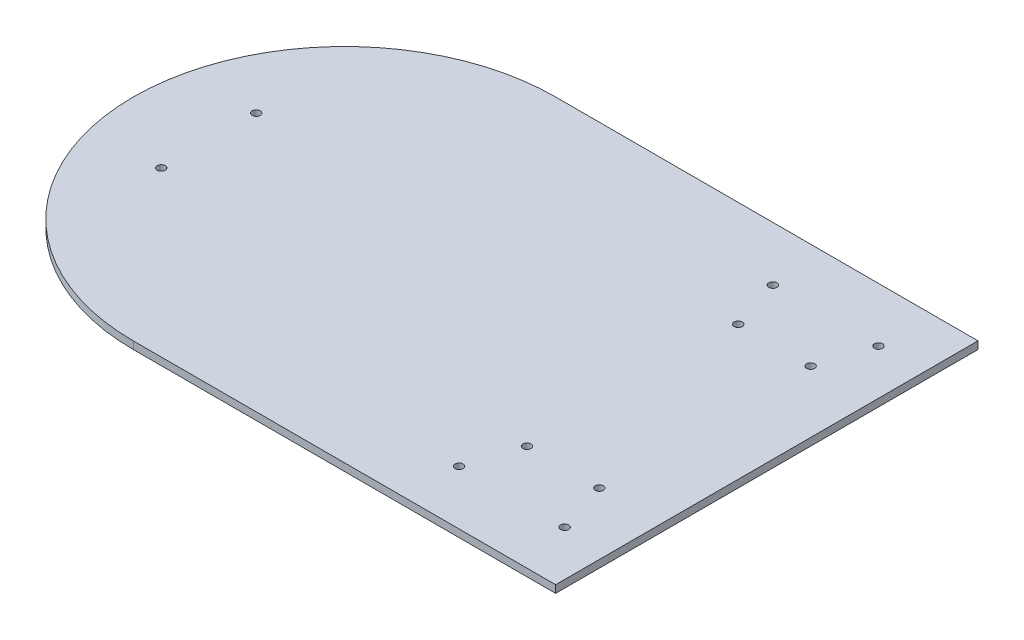
SolidWorks part; units mm, degrees
material "Acrylic (Medium-high impact)"
ref_plane "Front Plane" through (0, 0, 0) normal (0, 0, 1) x (1, 0, 0)
ref_plane "Top Plane" through (0, 0, 0) normal (0, 1, 0) x (1, 0, 0)
ref_plane "Right Plane" through (0, 0, 0) normal (1, 0, 0) x (0, 0, -1)
sketch "Sketch2" plane through (0, 0, 0) normal (0, 1, 0) x (1, 0, 0)
  line L0 (0, 0) -> (0, 177.8)
  line L1 (0, 177.8) -> (-177.8, 177.8)
  line L2 (0, 0) -> (-177.8, 0)
  line L3 (-177.8, 177.8) -> (-177.8, 0) construction
  arc A0 (-177.8, 177.8) -> (-177.8, 0) centre (-177.8, 88.9) ccw
  dimension "D1" = 177.8
  dimension "D2" = 177.8
extrude "Boss-Extrude1" add sketch "Sketch2" along normal blind 3.175
sketch "Motor/Caster Mount Hole Locations" plane through (0, 0, 0) normal (0, 1, 0) x (1, 0, 0)
  line L0 (0, 0) -> (0, 177.8) construction
  line L5 (-234.95, 108.9) -> (-234.95, 68.9) construction
  line L6 (0, 88.9) -> (-266.7, 88.9) construction
  line L11 (-63.5, 154.9552) -> (-19.05, 154.9552) construction
  line L12 (-56.515, 133.3652) -> (-26.035, 133.3652) construction
  line L13 (-41.275, 133.3652) -> (-41.275, 154.9552) construction
  line L14 (0, 177.8) -> (-177.8, 177.8) construction
  line L15 (-56.515, 44.4348) -> (-26.035, 44.4348) construction
  line L16 (-41.275, 44.4348) -> (-41.275, 22.8448) construction
  line L17 (-63.5, 22.8448) -> (-19.05, 22.8448) construction
  arc A0 (-177.8, 177.8) -> (-177.8, 0) centre (-177.8, 88.9) ccw construction
  point P31 (-234.95, 88.9)
  dimension "D1" = 21.59
  dimension "D2" = 44.45
  dimension "D3" = 30.48
  dimension "D4" = 22.8448
  dimension "D5" = 19.05
  dimension "D6" = 40
  dimension "D7" = 31.75
hole_wizard "M3 Clearance Hole1" positions "Sketch3" profile "Sketch4" hole size "M3" standard "ANSI Metric" end condition through all
sketch "Sketch3" plane through (0, 3.175, 0) normal (0, 1, 0) x (1, 0, 0)
  point P0 (-63.5, 154.9552)
  point P3 (-19.05, 154.9552)
  point P6 (-56.515, 133.3652)
  point P9 (-26.035, 133.3652)
  point P12 (-56.515, 44.4348)
  point P15 (-26.035, 44.4348)
  point P18 (-63.5, 22.8448)
  point P21 (-19.05, 22.8448)
  point P24 (-234.95, 108.9)
  point P27 (-234.95, 68.9)
sketch "Sketch4" plane through (-63.5, 3.175, -154.9552) normal (1, 0, 0) x (0, 0, 1)
  line L0 (0, 0) -> (0, 3.175)
  line L1 (0, 3.175) -> (1.7, 3.175)
  line L2 (1.7, 3.175) -> (1.7, 0)
  line L5 (1.7, 0) -> (0, 0)
  line L11 (0, -6.35) -> (0, 107.95) construction
  dimension "Thru Hole Dia." = 3.4
  dimension "Thru Hole Depth" = 3.175
